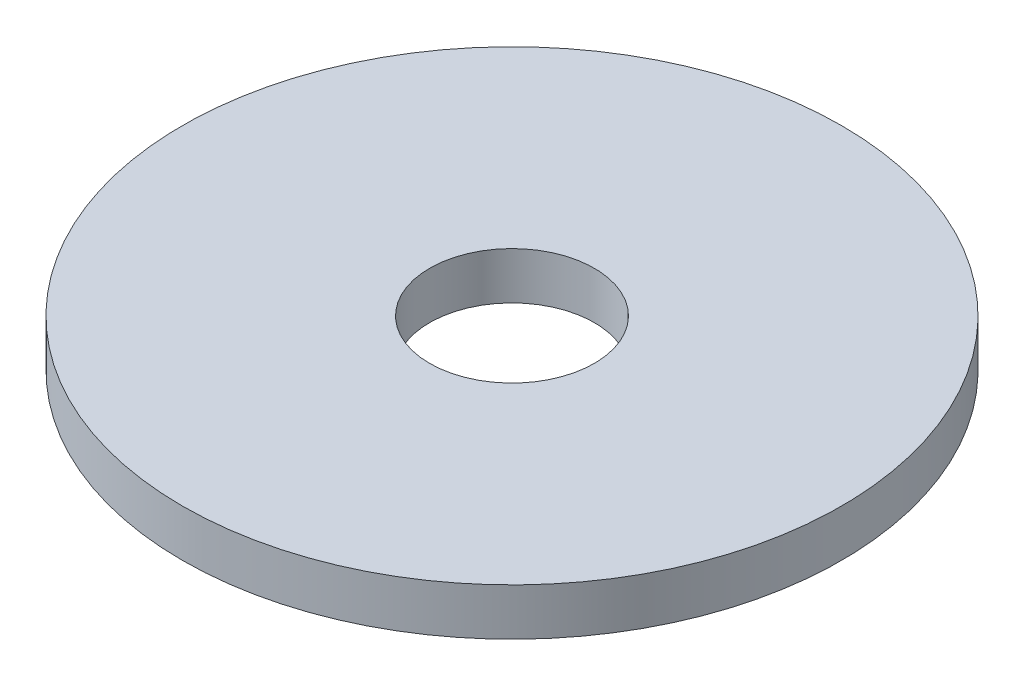
SolidWorks part; units mm, degrees
ref_plane "Front Plane" through (0, 0, 0) normal (0, 0, 1) x (1, 0, 0)
ref_plane "Top Plane" through (0, 0, 0) normal (0, 1, 0) x (1, 0, 0)
ref_plane "Right Plane" through (0, 0, 0) normal (1, 0, 0) x (0, 0, -1)
sketch "Sketch1" plane through (0, 0, 0) normal (0, 1, 0) x (1, 0, 0)
  circle A0 centre (0, 0) radius 70
  circle A1 centre (0, 0) radius 17.5
extrude "Boss-Extrude1" add sketch "Sketch1" along normal mid plane 10
